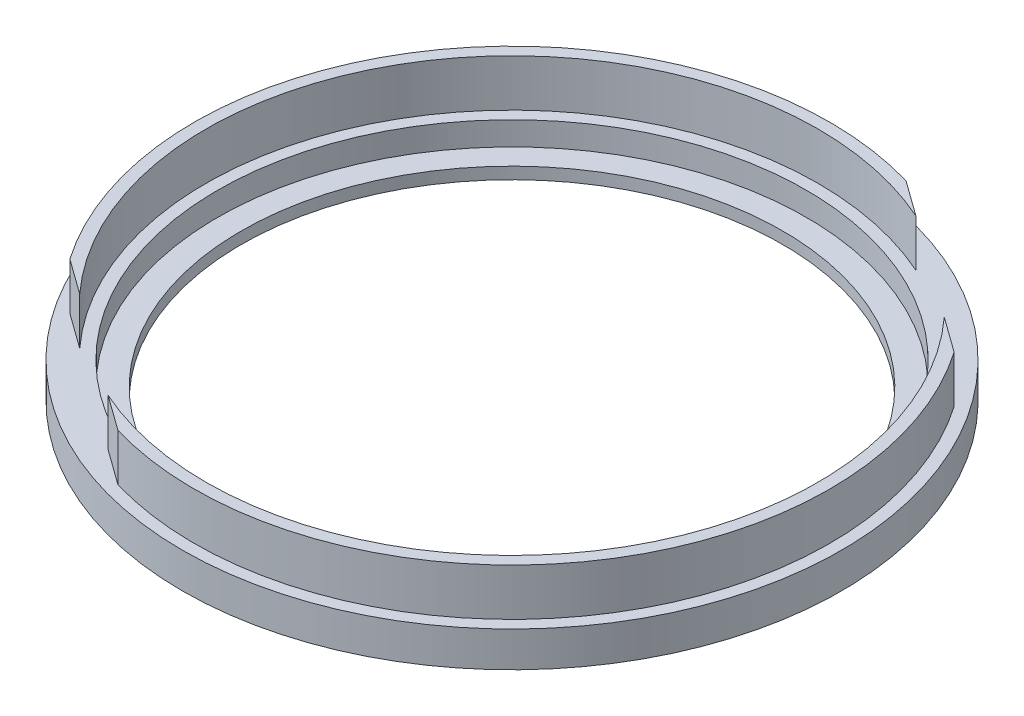
SolidWorks part; units mm, degrees
ref_plane "Plan de face" through (0, 0, 0) normal (0, 0, 1) x (1, 0, 0)
ref_plane "Plan de dessus" through (0, 0, 0) normal (0, 1, 0) x (1, 0, 0)
ref_plane "Plan de droite" through (0, 0, 0) normal (1, 0, 0) x (0, 0, -1)
sketch "Esquisse6" plane through (0, 0, 0) normal (0, 1, 0) x (1, 0, 0)
  circle A0 centre (-49.2601, 37.6293) radius 28
  dimension "D1" = 56
extrude "Boss.-Extru.3" add sketch "Esquisse6" along normal blind 3
sketch "Esquisse7" plane through (0, 3, 0) normal (0, 1, 0) x (1, 0, 0)
  circle A1 centre (-49.2601, 37.6293) radius 26
  circle A2 centre (-49.2601, 37.6293) radius 27
  circle A3 centre (-49.2601, 37.6293) radius 27
  dimension "D1" = 1
  dimension "D2" = 1
extrude "Boss.-Extru.4" add sketch "Esquisse7" along normal blind 4
sketch "Esquisse8" plane through (0, 3, 0) normal (0, 1, 0) x (1, 0, 0)
  circle A2 centre (-49.2601, 37.6293) radius 25
  circle A3 centre (-49.2601, 37.6293) radius 25
  dimension "D1" = 1
extrude "Enlèv. mat.-Extru.2" cut sketch "Esquisse8" against normal blind 2
sketch "Esquisse9" plane through (0, 1, 0) normal (0, 1, 0) x (1, 0, 0)
  circle A2 centre (-49.2601, 37.6293) radius 23
  circle A3 centre (-49.2601, 37.6293) radius 23
  dimension "D1" = 2
extrude "Enlèv. mat.-Extru.3" cut sketch "Esquisse9" against normal through all
sketch "Esquisse10" plane through (0, 7, 0) normal (0, 1, 0) x (1, 0, 0)
  line L0 (-71.4689, 22.2745) -> (-56.8215, 11.7097)
  line L1 (-71.4689, 22.2745) -> (-74.029, 18.7251)
  line L2 (-74.029, 18.7251) -> (-59.3816, 8.1602)
  line L3 (-59.3816, 8.1602) -> (-56.8215, 11.7097)
  line L4 (-49.2601, 37.6293) -> (-66.1804, 49.8334) construction
  line L11 (-39.1387, 67.0983) -> (-24.4913, 56.5335)
  line L12 (-41.6988, 63.5489) -> (-39.1387, 67.0983)
  line L13 (-41.6988, 63.5489) -> (-27.0514, 52.9841)
  line L14 (-24.4913, 56.5335) -> (-27.0514, 52.9841)
  circle A0 centre (-49.2601, 37.6293) radius 27 construction
  dimension "D1" = 18.06
extrude "Enlèv. mat.-Extru.4" cut sketch "Esquisse10" against normal blind 4
